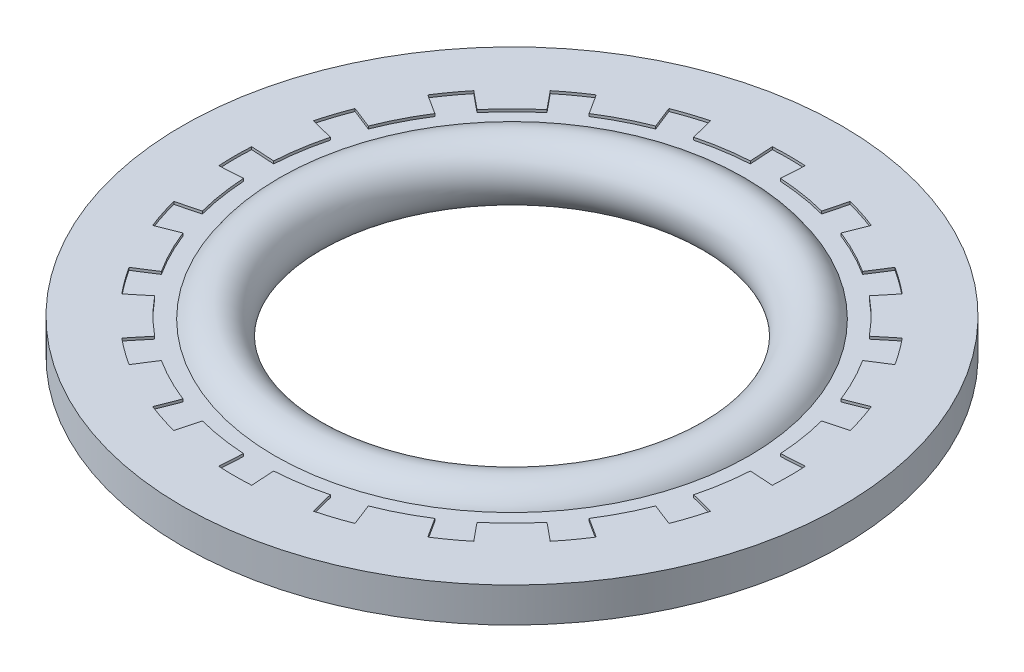
SolidWorks part; units mm, degrees
ref_plane "Front Plane" through (0, 0, 0) normal (0, 0, 1) x (1, 0, 0)
ref_plane "Top Plane" through (0, 0, 0) normal (0, 1, 0) x (1, 0, 0)
ref_plane "Right Plane" through (0, 0, 0) normal (1, 0, 0) x (0, 0, -1)
sketch "Sketch1" plane through (0, 0, 0) normal (0, 0, 1) x (1, 0, 0)
  line L0 (-9.652, 0) -> (9.652, 0) construction
  line L1 (0, 0) -> (0, 0.508) construction
  line L3 (-9.652, 0.508) -> (-6.1976, 0.508)
  line L4 (-9.652, 0.508) -> (-9.652, -0.508)
  line L5 (-9.652, -0.508) -> (-6.1976, -0.508)
  line L6 (-6.1976, 0.508) -> (-6.1976, -0.508)
  circle A0 centre (-6.1976, 0) radius 0.8636
  point P3 (-5.334, 0)
  dimension "D1" = 1.7272
  dimension "D2" = 14.1224
  dimension "ID" = 10.668
  dimension "thickness" = 1.016
  dimension "OD" = 19.304
sketch "Sketch2" plane through (0, 0, 0) normal (0, 0, 1) x (1, 0, 0)
  line L0 (-9.652, 0.508) -> (-9.652, -0.508) construction
  line L2 (-9.652, 0.508) -> (-6.1976, 0.508) construction
  line L3 (-9.652, -0.508) -> (-6.1976, -0.508) construction
  line L4 (-9.652, 0.508) -> (-9.652, -0.508)
  line L5 (-7.4354, 0.508) -> (-7.4354, -0.508)
  line L6 (-9.652, 0.508) -> (-7.4354, 0.508)
  line L7 (-9.652, -0.508) -> (-7.4354, -0.508)
  line L8 (0, 0) -> (0, 0.508) construction
  line L9 (0, 0) -> (0, 0.508) construction
  line L10 (-7.0612, 0.508) -> (-7.0612, -0.508) construction
  circle A0 centre (-6.1976, 0) radius 0.8636 construction
  dimension "D1" = 14.8709
revolve "Revolve1" add sketch "Sketch2" angle 360 about L9
sketch "Sketch3" plane through (0, 0.508, 0) normal (0, 1, 0) x (1, 0, 0)
  line L0 (-0.4419, 7.4223) -> (-0.4826, 8.106)
  line L1 (0.4419, 7.4223) -> (0.4826, 8.106)
  circle A0 centre (0, 0) radius 8.1204 construction
  circle A1 centre (0, 0) radius 7.4354 construction
  arc A3 (0.4826, 8.106) -> (-0.4826, 8.106) centre (0, 0) ccw
  arc A4 (0.4419, 7.4223) -> (-0.4419, 7.4223) centre (0, 0) ccw
  dimension "D1" = 16.2408
  dimension "D2" = 0.9652
extrude "Cut-Extrude1" cut sketch "Sketch3" against normal through all
pattern_circular "CirPattern1" count 20 over 360 about axis through (0, 0, 0) along (0, 1, 0) of "Cut-Extrude1"
sketch "Sketch4" plane through (0, 0, 0) normal (0, 0, 1) x (1, 0, 0)
  line L3 (-8.1204, -0.4318) -> (-6.9455, -0.4318)
  line L4 (-8.1204, 0.4318) -> (-6.9455, 0.4318)
  line L5 (-8.1204, 0.4318) -> (-8.1204, -0.4318)
  line L6 (0, 0) -> (0, 0.508) construction
  line L7 (0, 0) -> (0, 0.508) construction
  circle A0 centre (-6.1976, 0) radius 0.8636 construction
  arc A1 (-6.9455, -0.4318) -> (-6.9455, 0.4318) centre (-6.1976, 0) ccw
  dimension "D1" = 0.8636
  dimension "D2" = 16.2408
revolve "Revolve2" add sketch "Sketch4" angle 360 about L7
sketch "Sketch5" plane through (0, 0, 0) normal (0, 1, 0) x (1, 0, 0)
  circle A0 centre (0, 0) radius 5.334
  circle A1 centre (0, 0) radius 9.652 construction
  circle A2 centre (0, 0) radius 9.652
equation "\"D1@Sketch1\" = \"thickness@Sketch1\"*1.7"
equation "\"D2@Sketch3\" = \"OD@Sketch1\"/20"
equation "\"D1@Sketch4\" = \"thickness@Sketch1\"*.85"
equation "\"D1@Sketch3\" = \"D2@Sketch1\"*1.15"
equation "\"D1@Sketch2\" = \"D2@Sketch1\"*1.053"
equation "\"D2@Sketch4\" = \"D1@Sketch3\""
